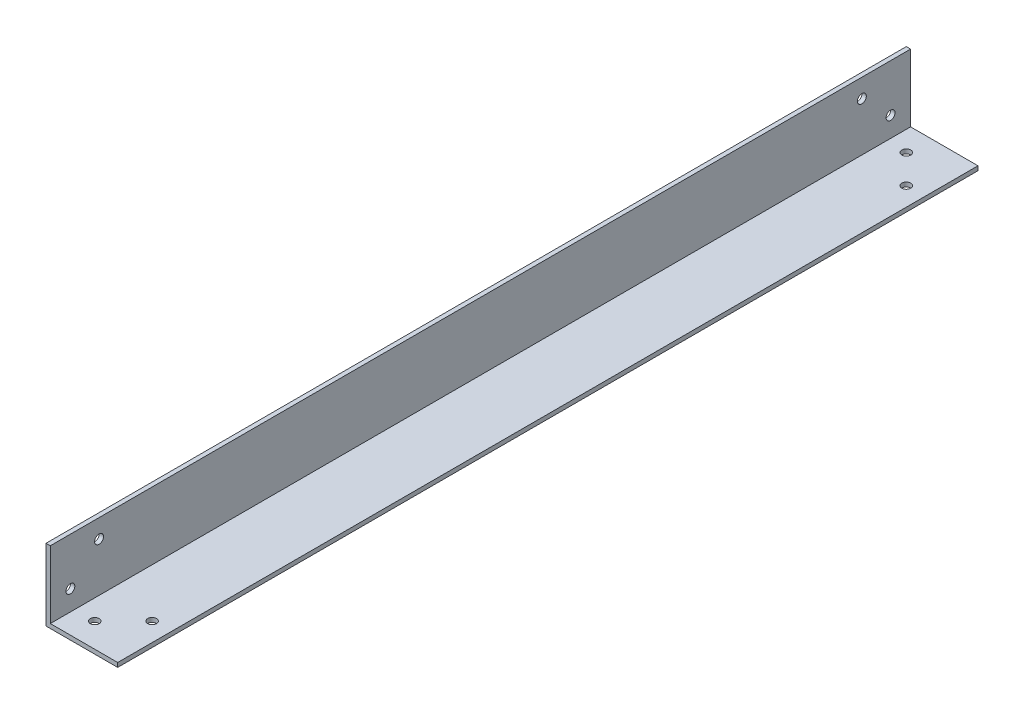
SolidWorks part; units mm, degrees
ref_plane "Front Plane" through (0, 0, 0) normal (0, 0, 1) x (1, 0, 0)
ref_plane "Top Plane" through (0, 0, 0) normal (0, 1, 0) x (1, 0, 0)
ref_plane "Right Plane" through (0, 0, 0) normal (1, 0, 0) x (0, 0, -1)
sketch "Sketch1" plane through (0, 0, 0) normal (0, 0, 1) x (1, 0, 0)
  line L0 (0, 0) -> (0, 25)
  line L1 (0, 25) -> (1.5, 25)
  line L2 (1.5, 25) -> (1.5, 1.5)
  line L3 (1.5, 1.5) -> (25, 1.5)
  line L4 (25, 1.5) -> (25, 0)
  line L5 (25, 0) -> (0, 0)
  dimension "D1" = 1.5
  dimension "D2" = 25
extrude "Boss-Extrude1" add sketch "Sketch1" along normal blind 300
sketch "Sketch2" plane through (0, 0, 0) normal (-1, 0, 0) x (0, 0, 1)
  line L0 (293, 8.5) -> (7, 8.5) construction
  line L1 (17, 18.5) -> (283, 18.5) construction
  line L2 (300, 25) -> (0, 25) construction
  line L3 (0, 25) -> (0, 0) construction
  line L4 (300, 25) -> (300, 0) construction
  circle A0 centre (283, 18.5) radius 1.55
  circle A1 centre (293, 8.5) radius 1.55
  circle A2 centre (17, 18.5) radius 1.55
  circle A3 centre (7, 8.5) radius 1.55
  dimension "D1" = 3.1
  dimension "D2" = 6.5
  dimension "D3" = 16.5
  dimension "D4" = 7
  dimension "D5" = 17
  dimension "D6" = 17
  dimension "D7" = 7
extrude "Cut-Extrude1" cut sketch "Sketch2" against normal blind 10
sketch "Sketch3" plane through (0, 0, 0) normal (0, -1, 0) x (1, 0, 0)
  line L0 (18.5, 18.5) -> (18.5, 281.5) construction
  line L1 (8.5, 291.5) -> (8.5, 8.5) construction
  line L2 (25, 300) -> (25, 0) construction
  line L3 (0, 300) -> (25, 300) construction
  line L4 (0, 0) -> (25, 0) construction
  circle A0 centre (18.5, 281.5) radius 1.55
  circle A1 centre (8.5, 291.5) radius 1.55
  circle A2 centre (18.5, 18.5) radius 1.55
  circle A3 centre (8.5, 8.5) radius 1.55
  dimension "D7" = 3.1
  dimension "D1" = 6.5
  dimension "D2" = 16.5
  dimension "D3" = 18.5
  dimension "D4" = 8.5
  dimension "D5" = 8.5
  dimension "D6" = 18.5
extrude "Cut-Extrude2" cut sketch "Sketch3" against normal blind 10
